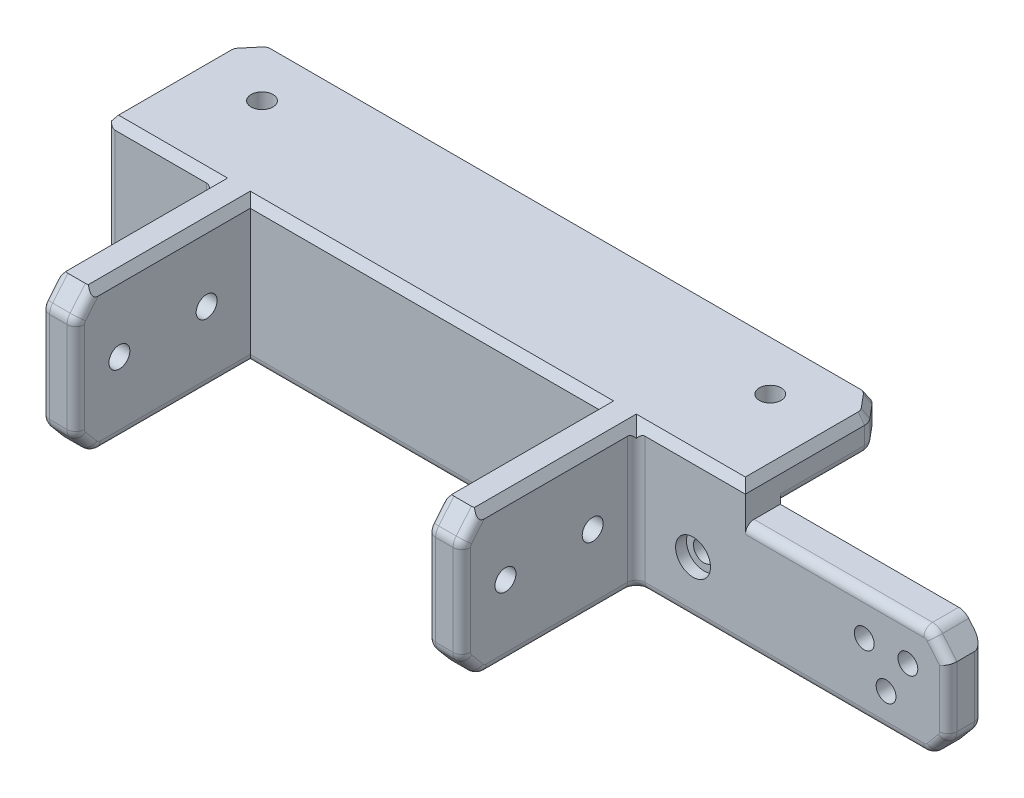
SolidWorks part; units mm, degrees
ref_plane "Front Plane" through (0, 0, 0) normal (0, 0, 1) x (1, 0, 0)
ref_plane "Top Plane" through (0, 0, 0) normal (0, 1, 0) x (1, 0, 0)
ref_plane "Right Plane" through (0, 0, 0) normal (1, 0, 0) x (0, 0, -1)
sketch "Sketch1" plane through (0, 0, 0) normal (0, 1, 0) x (1, 0, 0)
  line L1 (119.75, 0) -> (119.75, -8)
  line L2 (119.75, -8) -> (48.25, -8)
  line L3 (48.25, -8) -> (48.25, -48)
  line L4 (48.25, -48) -> (40.25, -48)
  line L5 (40.25, -48) -> (40.25, -8)
  line L6 (40.25, -8) -> (-40.25, -8)
  line L7 (-40.25, -8) -> (-40.25, -48)
  line L8 (-40.25, -48) -> (-48.25, -48)
  line L9 (-48.25, -48) -> (-48.25, -8)
  line L10 (-48.25, -8) -> (-73.25, -8)
  line L11 (-73.25, -8) -> (-73.25, 0)
  line L12 (119.75, 0) -> (-73.25, 0)
  point P14 (0, -8)
  dimension "D1" = 8
  dimension "D2" = 8
  dimension "D3" = 80.5
  dimension "D4" = 40
  dimension "D5" = 25
  dimension "D6" = 79.5
extrude "Boss-Extrude1" add sketch "Sketch1" along normal mid plane 25
sketch "Sketch2" plane through (0, 0, 8) normal (0, 0, 1) x (1, 0, 0)
  line L1 (-73.25, 12.5) -> (-73.25, -12.5) construction
  line L2 (-73.25, 0) -> (-61.25, 0) construction
  line L3 (0, -13.75) -> (0, 13.75) construction
  circle A0 centre (-61.25, 0) radius 2.4
  circle A2 centre (61.25, 0) radius 2.4
  dimension "D2" = 4.8
  dimension "D1" = 12
extrude "Cut-Extrude1" cut sketch "Sketch2" against normal through all
sketch "Sketch4" plane through (0, 12.5, 0) normal (0, 1, 0) x (1, 0, 0)
  line L1 (-73.25, -8) -> (-48.25, -8)
  line L2 (-73.25, -8) -> (-73.25, 25.4)
  line L3 (-73.25, 25.4) -> (73.25, 25.4)
  line L4 (73.25, -8) -> (73.25, 25.4)
  line L5 (119.75, 0) -> (-73.25, 0) construction
  line L6 (-73.25, 12.7) -> (-58.25, 12.7) construction
  line L7 (58.25, 12.7) -> (73.25, 12.7) construction
  line L8 (-40.25, -8) -> (40.25, -8)
  line L10 (-48.25, -8) -> (-48.25, -48)
  line L11 (-48.25, -48) -> (-40.25, -48)
  line L12 (-40.25, -8) -> (-40.25, -48)
  line L14 (40.25, -8) -> (40.25, -48)
  line L15 (40.25, -48) -> (48.25, -48)
  line L16 (48.25, -8) -> (48.25, -48)
  line L18 (73.25, -8) -> (48.25, -8)
  circle A0 centre (-58.25, 12.7) radius 2.5
  circle A1 centre (58.25, 12.7) radius 2.5
  point P5 (73.25, -14.2952)
  dimension "D3" = 5
  dimension "D4" = 12.7
  dimension "D1" = 25.4
  dimension "D2" = 15
extrude "Boss-Extrude2" add sketch "Sketch4" along normal blind 8
sketch "Sketch3" plane through (-48.25, 0, 0) normal (-1, 0, 0) x (0, 0, 1)
  line L1 (8, 20.5) -> (8, -12.5) construction
  line L2 (48, 20.5) -> (48, -12.5) construction
  circle A0 centre (18, 4) radius 2.4
  circle A1 centre (38, 4) radius 2.4
  point P8 (48, 4)
  dimension "D3" = 4.8
  dimension "D1" = 10
  dimension "D2" = 20
extrude "Cut-Extrude2" cut sketch "Sketch3" against normal through all
sketch "Sketch5" plane through (0, 0, 8) normal (0, 0, 1) x (1, 0, 0)
  circle A0 centre (-61.25, 0) radius 4
  circle A1 centre (61.25, 0) radius 4
  circle A3 centre (61.25, 0) radius 2.4 construction
  point P6 (0, 0)
  dimension "D1" = 8
extrude "Cut-Extrude3" cut sketch "Sketch5" against normal blind 2.5
sketch "Sketch8" plane through (0, 0, 8) normal (0, 0, 1) x (1, 0, 0)
  line L0 (110.5, 3.5) -> (100.5, 3.5) construction
  line L1 (105.5, 3.5) -> (105.5, -4.5) construction
  line L2 (48.25, -12.5) -> (119.75, -12.5) construction
  circle A0 centre (100.5, 3.5) radius 2.275
  circle A1 centre (110.5, 3.5) radius 2.275
  circle A2 centre (105.5, -4.5) radius 2.275
  dimension "D3" = 4.55
  dimension "D1" = 10
  dimension "D2" = 8
  dimension "D4" = 105.5
  dimension "D5" = 8
extrude "Cut-Extrude4" cut sketch "Sketch8" against normal up to next
chamfer "Chamfer1" distance 5 angle 40 9 edges at (119.75, 12.5, 4) (119.75, -12.5, 4) (-73.25, -12.5, 4) (44.25, -12.5, 48) (-44.25, -12.5, 48) (44.25, 20.5, 48) (-44.25, 20.5, 48) (73.25, 16.5, -25.4) (-73.25, 16.5, -25.4)
fillet "Fillet1" radius 3 15 edges at (44.25, -7.5, 48) (-44.25, -7.5, 48) (-73.25, -7.5, 4) (119.75, -7.5, 4) (44.25, 15.5, 48) (-44.25, 15.5, 48) (44.25, -12.5, 43.8045) (-44.25, -12.5, 43.8045) (115.5545, -12.5, 4) (-69.0545, -12.5, 4) (69.0545, 16.5, -25.4) (-73.25, 16.5, -20.4) (-69.0545, 16.5, -25.4) (73.25, 16.5, -20.4) (115.5545, 12.5, 4)
chamfer "Chamfer2" distance 2 angle 35 16 edges at (60.75, 20.5, 8) (48.25, 20.5, 25.9023) (40.25, 20.5, 25.9023) (0, 20.5, 8) (-40.25, 20.5, 25.9023) (73.25, 20.5, -5.654) (71.2509, 20.5, -22.7824) (68.9234, 20.5, -25.1189) (0, 20.5, -25.4) (-68.9234, 20.5, -25.1189) (-71.2509, 20.5, -22.7824) (-73.0691, 20.5, -20.3341) (-48.25, 20.5, 25.9023) (-60.75, 20.5, 8) (-73.25, 20.5, -5.654) (73.0691, 20.5, -20.3341)
fillet "Fillet2" radius 2 62 edges at (-73.25, 6.046, 8) (-73.0691, -7.4341, 8) (-71.2509, -9.8824, 8) (-68.9234, -12.2189, 8) (-57.9528, -12.5, 8) (119.5691, -7.4341, 8) (117.7509, -9.8824, 8) (115.4234, -12.2189, 8) (119.75, 0.546, 0) (119.5691, -7.4341, 0) (117.7509, -9.8824, 0) (115.4234, -12.2189, 0) (-73.25, 3.046, 0) (-73.0691, -7.4341, 0) (-71.2509, -9.8824, 0) (-68.9234, -12.2189, 0) (73.25, 12.5, -9.654) (71.2509, 12.5, -22.7824) (68.9234, 12.5, -25.1189) (0, 12.5, -25.4) (-68.9234, 12.5, -25.1189) (-71.2509, 12.5, -22.7824) (-73.0691, 12.5, -20.3341) (48.25, 17.4182, 46.3904) (48.25, 15.4341, 47.8191) (48.25, -12.5, 25.2028) (48.25, -12.2189, 43.6734) (48.25, -9.8824, 46.0009) (48.25, -7.4341, 47.8191) (40.25, 17.4182, 46.3904) (40.25, 15.4341, 47.8191) (40.25, -12.5, 25.2028) (40.25, -12.2189, 43.6734) (40.25, -9.8824, 46.0009) (40.25, -7.4341, 47.8191) (-40.25, 17.4182, 46.3904) (-40.25, 15.4341, 47.8191) (-40.25, -12.5, 25.2028) (-40.25, -12.2189, 43.6734) (-40.25, -9.8824, 46.0009) (-40.25, -7.4341, 47.8191) (-48.25, -12.5, 25.2028) (-48.25, -12.2189, 43.6734) (-48.25, -9.8824, 46.0009) (-48.25, -7.4341, 47.8191) (-48.25, 4, 48) (-48.25, 15.4341, 47.8191) (48.25, 3, 8) (81.2028, -12.5, 8) (0, -12.5, 8) (23.25, -12.5, 0) (-73.25, 12.5, -9.654) (-48.25, 3, 8) (48.25, 4, 48) (40.25, 4, 48) (-40.25, 4, 48) (-48.25, 17.4182, 46.3904) (119.75, 0.546, 8) (73.0691, 12.5, -20.3341) (118.1019, 9.4642, 8) (115.4234, 12.2189, 8) (93.7028, 12.5, 8)
